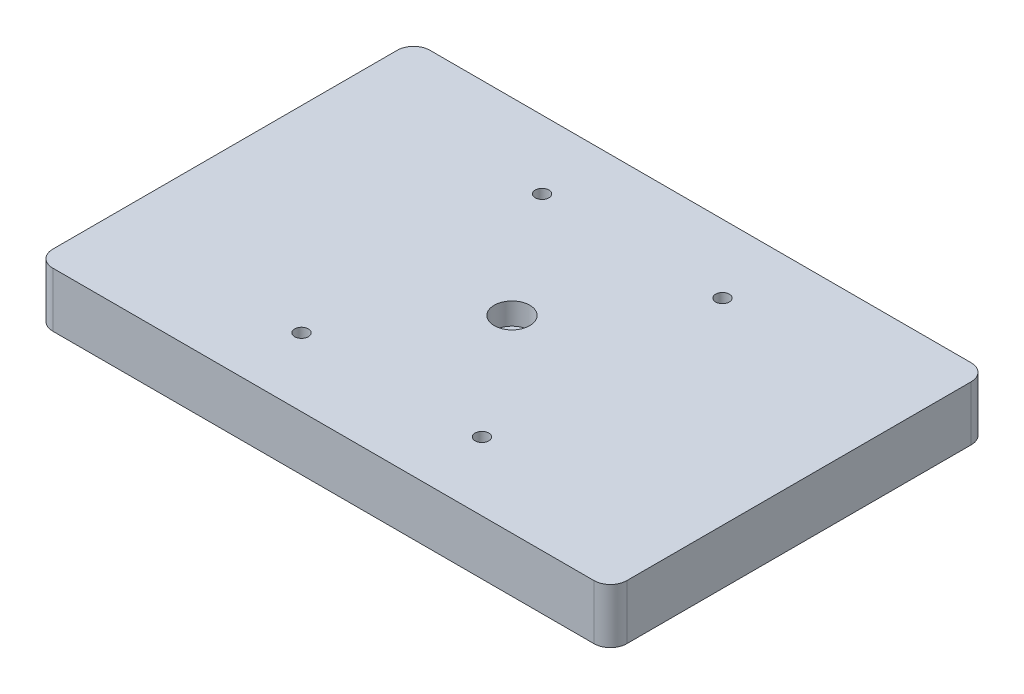
SolidWorks part; units mm, degrees
material "6061 Alloy"
ref_plane "Front Plane" through (0, 0, 0) normal (0, 0, 1) x (1, 0, 0)
ref_plane "Top Plane" through (0, 0, 0) normal (0, 1, 0) x (1, 0, 0)
ref_plane "Right Plane" through (0, 0, 0) normal (1, 0, 0) x (0, 0, -1)
sketch "Sketch1" plane through (0, 0, 0) normal (0, 1, 0) x (1, 0, 0)
  line L1 (-52.5, 34.5) -> (52.5, 34.5)
  line L2 (-52.5, 34.5) -> (-52.5, -34.5)
  line L3 (-52.5, -34.5) -> (52.5, -34.5)
  line L4 (52.5, 34.5) -> (52.5, -34.5)
  line L5 (-52.5, 34.5) -> (52.5, -34.5) construction
  line L6 (-52.5, -34.5) -> (52.5, 34.5) construction
  point P0 (0, 0)
  dimension "D1" = 105
  dimension "D2" = 69
extrude "Boss-Extrude1" add sketch "Sketch1" along normal blind 10
fillet "Fillet1" radius 3 4 edges at (-52.5, 5, -34.5) (52.5, 5, -34.5) (52.5, 5, 34.5) (-52.5, 5, 34.5)
hole_wizard "CBORE for M3 SHCS1" positions "Sketch2" profile "Sketch3" counterbore size "M3" standard "ANSI Metric" end condition through all
sketch "Sketch2" plane through (0, 10, 0) normal (0, 1, 0) x (1, 0, 0)
  line L0 (0, -5.5) -> (0, 5.5) construction
  line L1 (-5.5, 0) -> (5.5, 0) construction
  point P0 (0, 0)
sketch "Sketch3" plane through (0, 10, 0) normal (1, 0, 0) x (0, 0, 1)
  line L0 (0, 0) -> (0, 10)
  line L1 (0, 10) -> (1.7, 10)
  line L3 (1.7, 10) -> (1.7, 4)
  line L4 (1.7, 4) -> (3.25, 4)
  line L5 (3.25, 4) -> (3.25, 0)
  line L7 (3.25, 0) -> (0, 0)
  line L11 (0, -6.35) -> (0, 107.95) construction
  dimension "Thru Hole Dia." = 3.4
  dimension "Thru Hole Depth" = 10
  dimension "C'Bore Dia." = 6.5
  dimension "C'Bore Depth" = 4
hole_wizard "M3x0.5 Tapped Hole1" positions "Sketch4" profile "Sketch5" tap size "M3x0.5" standard "ANSI Metric"
sketch "Sketch4" plane through (0, 10, 0) normal (0, 1, 0) x (1, 0, 0)
  line L0 (-5.5, 0) -> (5.5, 0) construction
  line L1 (0, -5.5) -> (0, 5.5) construction
  point P0 (16.5, -22)
  dimension "D1" = 22
  dimension "D2" = 16.5
cosmetic thread "Hole Thread1" parameters "D1"=8, "D2"=3
sketch "Sketch5" plane through (16.5, 10, 22) normal (1, 0, 0) x (0, 0, 1)
  line L0 (0, 0) -> (0, 10.7511)
  line L1 (0, 10.7511) -> (1.25, 10)
  line L2 (1.25, 10) -> (1.25, 0)
  line L5 (1.25, 0) -> (0, 0)
  line L10 (0, 10.7511) -> (-1.25, 10) construction
  line L11 (0, -6.35) -> (0, 107.95) construction
  dimension "Tap Drill Dia." = 2.5
  dimension "Tap Drill Depth" = 10
  dimension "Drill Angle" = 118
mirror "Mirror1" about plane through (0, 0, 0) normal (1, 0, 0) of "M3x0.5 Tapped Hole1"
mirror "Mirror2" about plane through (0, 0, 0) normal (0, 0, 1) of "Mirror1", "M3x0.5 Tapped Hole1"
